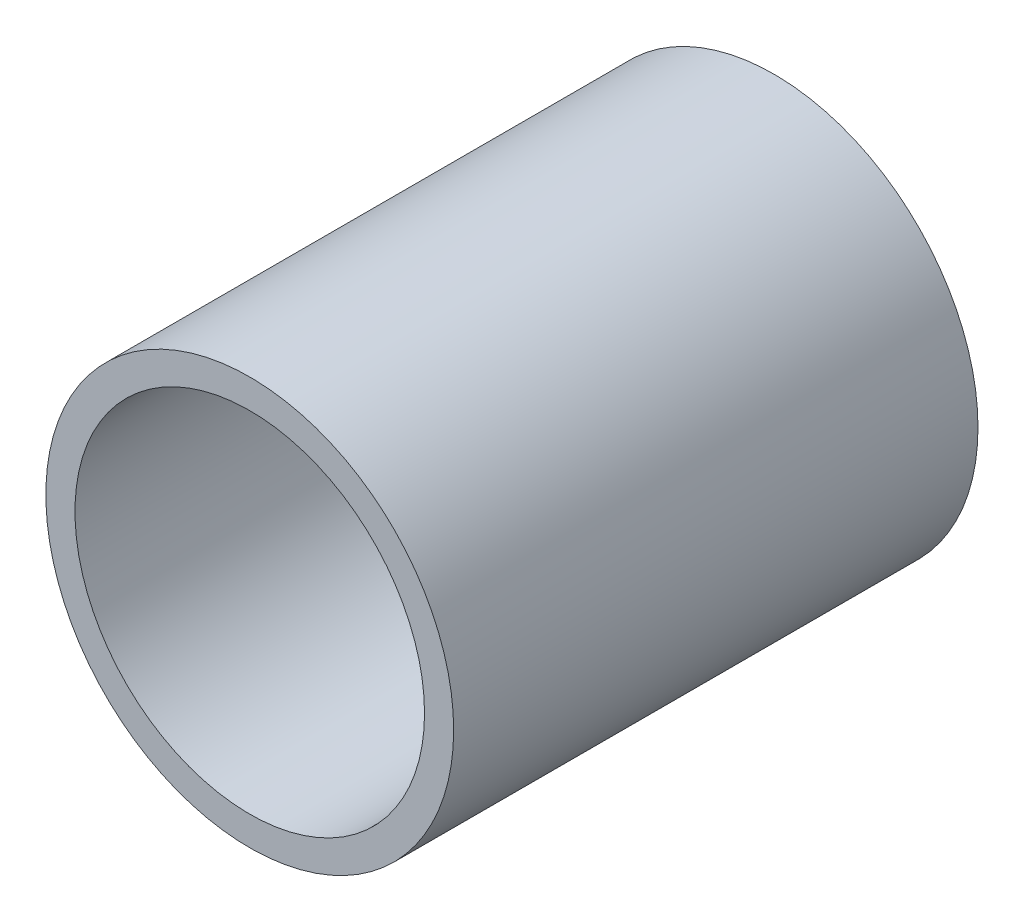
SolidWorks part; units mm, degrees
ref_plane "Front Plane" through (0, 0, 0) normal (0, 0, 1) x (1, 0, 0)
ref_plane "Top Plane" through (0, 0, 0) normal (0, 1, 0) x (1, 0, 0)
ref_plane "Right Plane" through (0, 0, 0) normal (1, 0, 0) x (0, 0, -1)
sketch "Sketch1" plane through (0, 0, 0) normal (0, 0, 1) x (1, 0, 0)
  circle A0 centre (0, 0) radius 38.1
  dimension "D1" = 76.2
extrude "Extrude-Thin1" add sketch "Sketch1" along normal blind 114.3 thin contours A0
